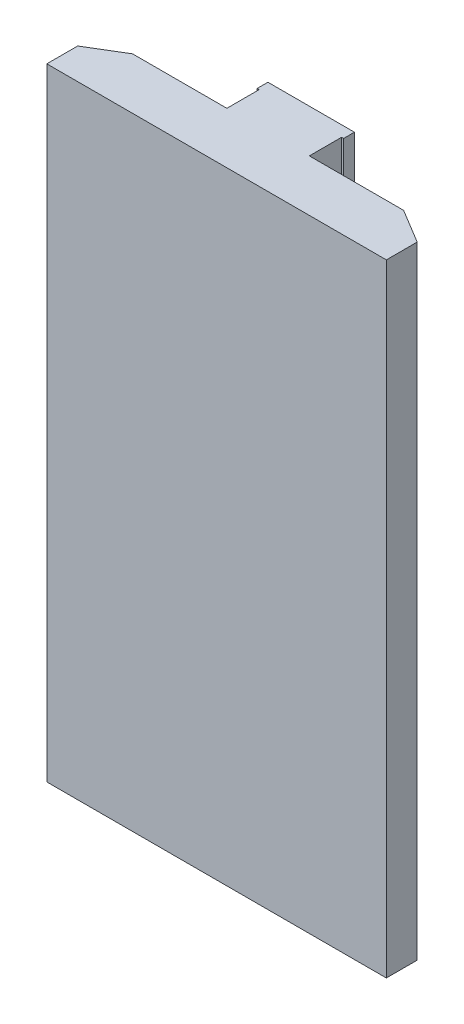
SolidWorks part; units mm, degrees
ref_plane "Front Plane" through (0, 0, 0) normal (0, 0, 1) x (1, 0, 0)
ref_plane "Top Plane" through (0, 0, 0) normal (0, 1, 0) x (1, 0, 0)
ref_plane "Right Plane" through (0, 0, 0) normal (1, 0, 0) x (0, 0, -1)
sketch "housing sketch" plane through (0, 0, 0) normal (0, 1, 0) x (1, 0, 0)
  line L0 (165.1, 0) -> (165.1, 30)
  line L1 (165.1, 30) -> (131.7953, 50.1)
  line L2 (131.7953, 50.1) -> (40.095, 50.1)
  line L3 (40.095, 50.1) -> (40.095, 81.5)
  line L4 (40.095, 81.5) -> (42.075, 81.5)
  line L5 (42.075, 81.5) -> (42.075, 92)
  line L6 (42.075, 92) -> (-42.075, 92)
  line L7 (-42.075, 92) -> (-42.075, 81.5)
  line L8 (-42.075, 81.5) -> (-40.095, 81.5)
  line L9 (-40.095, 81.5) -> (-40.095, 50.1)
  line L10 (-40.095, 50.1) -> (-131.7953, 50.1)
  line L11 (-131.7953, 50.1) -> (-165.1, 30)
  line L12 (-165.1, 30) -> (-165.1, 0)
  line L13 (-165.1, 0) -> (165.1, 0)
extrude "housing" add sketch "housing sketch" along normal mid plane 604.8
sketch "hanger hardware sketch" plane through (0, 0, 0) normal (0, 1, 0) x (1, 0, 0)
  line L0 (31.715, 91.5) -> (31.715, 96.32)
  line L1 (31.715, 96.32) -> (-31.715, 96.32)
  line L2 (-31.715, 96.32) -> (-31.715, 91.5)
  line L3 (-31.715, 91.5) -> (31.715, 91.5)
extrude "hanger hardware" add sketch "hanger hardware sketch" along normal mid plane 110
equation "\"diffL\"= 608.8mm"
equation "\"diffW\"= 329.4mm"
equation "\"diffT\"= 2.9mm"
equation "\"chanSlotW\"= 12.9mm"
equation "\"chanSlotDepth\"= 11.13mm"
equation "\"chanFloor\"= 1.57mm"
equation "\"chanLeg\"= 12.7mm"
equation "\"lightL\"= 604.8mm"
equation "\"lightW\"= 330.2mm"
equation "\"lightH\"= 92mm"
equation "\"lightSideFlat\"= 30mm"
equation "\"lightSlopeLen\"= 38.9mm"
equation "\"lightWingDepth\"= 50.1mm"
equation "\"lightWingFlat\"= 90.2mm"
equation "\"lightChanW\"= 99.6mm"
equation "\"lightChanStand\"= 44.1mm"
equation "\"insFlangeD\"= 12.3mm"
equation "\"insFromEnd\"= 20.7mm"
equation "\"insUpSlope\"= 20.8mm"
equation "\"gaugeH\"= 10mm"
equation "\"gaugeStepLen\"= 14mm"
equation "\"gaugeStepW0\"= 13.1mm"
equation "\"gaugeStepDW\"= 0.2mm"
equation "\"gaugeSteps\"= 5mm"
equation "\"gaugeHandleLen\"= 30mm"
equation "\"gaugeHandleW\"= 24mm"
equation "\"gaugeSlot0\"= 3mm"
equation "\"gaugeSlotD\"= 0.1mm"
equation "\"gaugeSlotDepth\"= 8mm"
equation "\"gap\"= 25.4mm"
equation "\"edgeL\"= 1mm"
equation "\"edgeW\"= 0.75mm"
equation "\"proud\"= 2.5mm"
equation "\"seatClr\"= 0.15mm"
equation "\"tongueClrZ\"= 0.1mm"
equation "\"tongueClrX\"= 0.25mm"
equation "\"tongueLen\"= 30mm"
equation "\"armSide\"= 45mm"
equation "\"armEnd\"= 20mm"
equation "\"brkW\"= 26mm"
equation "\"brkT\"= 7mm"
equation "\"brkSeatClr\"= 0.3mm"
equation "\"brkScrewSpan\"= 16mm"
equation "\"pilotD\"= 2.7mm"
equation "\"pilotDepth\"= 10mm"
equation "\"screwClrD\"= 3.9mm"
equation "\"jogBelow\"= 4mm"
equation "\"padT\"= 7mm"
equation "\"padLen\"= 36mm"
equation "\"m6Clr\"= 9mm"
equation "\"m6Slot\"= 5mm"
equation "\"flangeRelD\"= 18mm"
equation "\"flangeRelDepth\"= 1.5mm"
equation "\"relLen\"= 5mm"
equation "\"relDepth\"= 3.3mm"
equation "\"knockN\"= 100mm"
equation "\"petgcfE\"= 3000mm"
equation "\"mockExtent\"= 110mm"
equation "\"relZnear\"= 9.4mm"
equation "\"relZfar\"= 23.4mm"
equation "\"headD\"= 8mm"
equation "\"headH\"= 2.5mm"
equation "\"headFromEnd\"= 6.8mm"
equation "\"headBack\"= 16.4mm"
equation "\"sideClr\"= 0.4mm"
equation "\"cornerRelR\"= 1.5mm"
equation "\"cornerRelBack\"= 0.6mm"
equation "\"endHeadH\"= 2.8mm"
equation "\"footClr\"= 1.2mm"
equation "\"footEndClr\"= 3.5mm"
equation "\"footLift\"= 6mm"
equation "\"footBlockClr\"= 0.5mm"
equation "\"footBack\"= 50mm"
equation "\"footFwd\"= 10mm"
equation "\"footBraceEnd\"= 3mm"
equation "\"footLoadN\"= 25mm"
equation "\"spacerLen\"= 60mm"
equation "\"spacerShort\"= 0.5mm"
equation "\"spacerCham\"= 0.8mm"
equation "\"spacerPerSide\"= 3mm"
equation "\"spacerPerEnd\"= 1mm"
equation "\"toolR\"= 9mm"
equation "\"visR\"= 4mm"
equation "\"edgeR\"= 1mm"
equation "\"bendOutR\"= 5mm"
equation "\"insideR\"= 2.5mm"
equation "\"footCornerR\"= 10mm"
equation "\"footFrontR\"= 8mm"
equation "\"braceKinkR\"= 12mm"
equation "\"bedCham\"= 1mm"
equation "\"bedChamSmall\"= 0.6mm"
equation "\"soleTopR\"= 2mm"
equation "\"cornerR\"= 6mm"
equation "\"rimInR\"= 1mm"
equation "\"insFlangeH\"= 1mm"
equation "\"insHoleFinishD\" = 4.5mm"
equation "\"insLen\" = 6.4mm"
equation "\"cgInset\" = 4mm"
equation "\"lampWeightN\" = 51mm"
equation "\"frameWeightN\" = 10mm"
equation "\"bumpIn\" = 8mm"
equation "\"bumpH\" = 3mm"
equation "\"legBelowFront\" = 2mm"
equation "\"lipClr\" = 0.1mm"
equation "\"revealR\" = 2mm"
equation "\"frontCham\" = 1mm"
equation "\"leanDeg\" = 5mm"
equation "\"footTailT\" = 6mm"
equation "\"v1LeanDeg\" = 4.5mm"
equation "\"toeNoseR\" = 5mm"
equation "\"petgE\" = 2000mm"
equation "\"cheekT\" = 8mm"
equation "\"handleUp\" = 50mm"
equation "\"handleZ\" = -10mm"
equation "\"gripD\" = 19.05mm"
equation "\"gripClr\" = 0.5mm"
equation "\"bossWall\" = 5mm"
equation "\"bossLen\" = 14mm"
equation "\"socketFloor\" = 4mm"
equation "\"barEndClr\" = 1mm"
equation "\"lipH\" = 4mm"
equation "\"lipDeep\" = 6mm"
equation "\"stripT\" = 1.3mm"
equation "\"stripW\" = 12mm"
equation "\"stripClr\" = 0.5mm"
equation "\"stripBack\" = 3mm"
equation "\"endRelClr\" = 1mm"
equation "\"cornerScrewX\" = 5.5mm"
equation "\"cornerScrewZ\" = 6mm"
equation "\"cornerScrewD\" = 8.5mm"
equation "\"footTabIn\" = 33mm"
equation "\"footTabZ1\" = 50mm"
equation "\"footTabZ2\" = 19mm"
equation "\"footTabR\" = 8mm"
equation "\"landAx0\" = -17mm"
equation "\"landAz0\" = -30mm"
equation "\"landAx1\" = -3mm"
equation "\"landAz1\" = -18mm"
equation "\"landBx0\" = -60mm"
equation "\"landBz0\" = -43mm"
equation "\"landBx1\" = -46mm"
equation "\"landBz1\" = -27mm"
equation "\"sdLidW\" = 84.15mm"
equation "\"sdChanW\" = 80.19mm"
equation "\"sdLidStep\" = 1.7mm"
equation "\"sdInsRecess\" = 0.81mm"
equation "\"sdInsSpan\" = 59.21mm"
equation "\"sdJunkIn\" = 10.36mm"
equation "\"sdJunkH\" = 4.32mm"
equation "\"sdJunkLen\" = 110mm"
equation "\"sdHandleY\" = 0mm"
equation "\"sdInsDown\" = 21.3mm"
equation "\"sdSkirtH\" = 10.5mm"
equation "\"sdWallDown\" = 37mm"
equation "\"sdLidClr\" = 0.8mm"
equation "\"sdWasherT\" = 1.6mm"
equation "\"sdWasherD\" = 12mm"
equation "\"sdLegT\" = 5mm"
equation "\"sdLegBelow\" = 11mm"
equation "\"sdLegHalf\" = 46mm"
equation "\"sdSkirtSlope\" = 50mm"
equation "\"sdLipH\" = 5mm"
equation "\"sdLeadCham\" = 1mm"
equation "\"sdJunkSide\" = 1.5mm"
equation "\"sdRecessH\" = 6mm"
equation "\"sdRoofT\" = 6mm"
equation "\"sdOpenL\" = 114.3mm"
equation "\"sdOpenH\" = 50.8mm"
equation "\"sdGripD\" = 25mm"
equation "\"sdBendR\" = 18mm"
equation "\"sdBaseR\" = 8mm"
equation "\"sdEndMargin\" = 2mm"
equation "\"sdSlotW\" = 8mm"
equation "\"sdSlotFloat\" = 1mm"
equation "\"sdEdgeR\" = 2mm"
